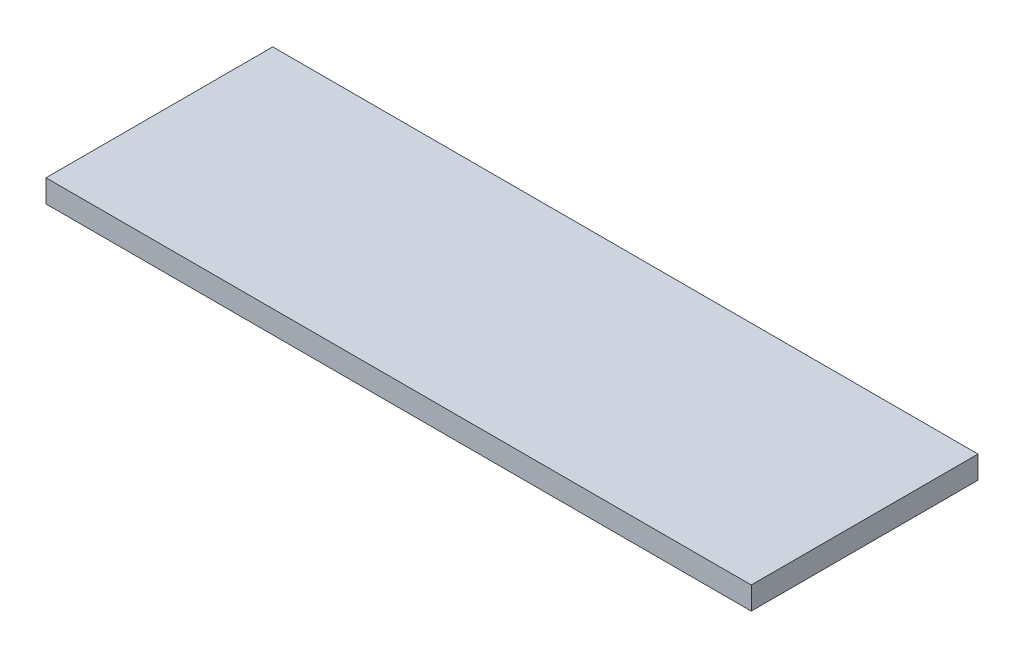
SolidWorks part; units mm, degrees
material "AISI 1020"
ref_plane "Front Plane" through (0, 0, 0) normal (0, 0, 1) x (1, 0, 0)
ref_plane "Top Plane" through (0, 0, 0) normal (0, 1, 0) x (1, 0, 0)
ref_plane "Right Plane" through (0, 0, 0) normal (1, 0, 0) x (0, 0, -1)
sketch "Sketch1" plane through (0, 0, 0) normal (0, 1, 0) x (1, 0, 0)
  line L1 (-150.6285, -16.5202) -> (99.3715, -16.5202)
  line L2 (-150.6285, -16.5202) -> (-150.6285, -56.5202)
  line L3 (-150.6285, -56.5202) -> (99.3715, -56.5202)
  line L4 (99.3715, -16.5202) -> (99.3715, -56.5202)
  dimension "D1" = 40
  dimension "D2" = 250
extrude "Boss-Extrude1" add sketch "Sketch1" along normal blind 4
sketch "Sketch2" plane through (0, 0, 0) normal (0, -1, 0) x (1, 0, 0)
  line L0 (99.3715, 16.5202) -> (-150.6285, 16.5202) construction
  line L1 (-26.214, 16.5202) -> (117.9294, 16.5202)
  line L2 (-26.214, 16.5202) -> (-26.214, 82.8557)
  line L3 (-26.214, 82.8557) -> (117.9294, 82.8557)
  line L4 (117.9294, 16.5202) -> (117.9294, 82.8557)
  line L5 (-29.214, 15.8728) -> (-29.214, 55.8728) construction
  dimension "D1" = 3
extrude "Cut-Extrude1" cut sketch "Sketch2" against normal blind 10
